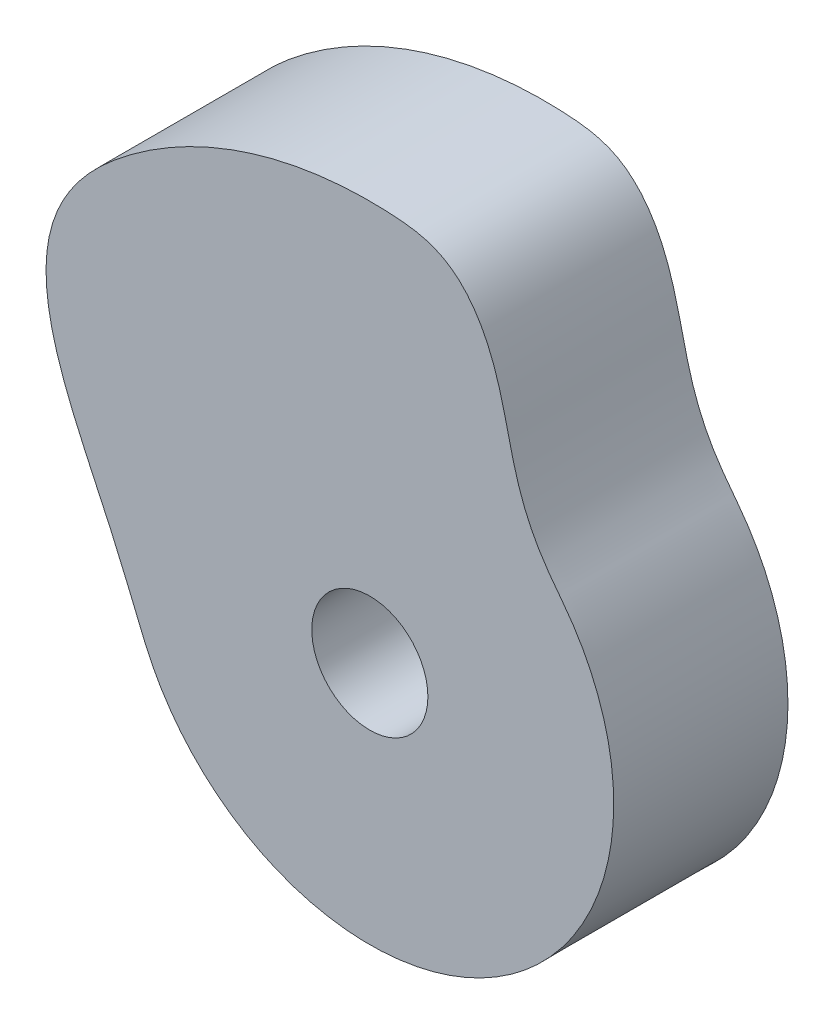
SolidWorks part; units mm, degrees
ref_plane "前视基准面" through (0, 0, 0) normal (0, 0, 1) x (1, 0, 0)
ref_plane "上视基准面" through (0, 0, 0) normal (0, 1, 0) x (1, 0, 0)
ref_plane "右视基准面" through (0, 0, 0) normal (1, 0, 0) x (0, 0, -1)
other "Configuration Table"
curve "曲线1"
sketch "草图1" plane through (0, 0, 0) normal (0, 0, 1) x (1, 0, 0)
  spline S0 degree 3 poles (34.8106, -23.5003) (35.0144, -23.1957) (35.2154, -22.8892) (35.4138, -22.581) (35.6096, -22.2712) (35.8026, -21.9596) (35.9929, -21.6463) (36.1804, -21.3313) (36.3651, -21.0148) (36.5472, -20.6967) (36.7264, -20.3769) (36.9028, -20.0557) (37.0764, -19.7328) (37.2472, -19.4086) (37.4151, -19.0828) (37.5801, -18.7555) (37.7425, -18.427) (37.9017, -18.0968) (38.0583, -17.7654) (38.2119, -17.4326) (38.3626, -17.0985) (38.5103, -16.7631) (38.6551, -16.4264) (38.797, -16.0884) (38.9359, -15.7492) (39.0719, -15.4089) (39.2049, -15.0673) (39.3348, -14.7246) (39.4618, -14.3808) (39.5858, -14.0359) (39.7068, -13.6899) (39.8248, -13.3429) (39.9397, -12.9949) (40.0516, -12.6459) (40.1604, -12.2958) (40.2662, -11.9449) (40.3689, -11.593) (40.4685, -11.2403) (40.565, -10.8867) (40.6585, -10.5323) (40.749, -10.1771) (40.8361, -9.8211) (40.9203, -9.4644) (41.0013, -9.107) (41.0792, -8.7488) (41.154, -8.39) (41.2256, -8.0306) (41.2941, -7.6705) (41.3596, -7.3099) (41.4217, -6.9487) (41.4808, -6.5869) (41.5367, -6.2247) (41.5894, -5.862) (41.639, -5.4988) (41.6854, -5.1353) (41.7286, -4.7713) (41.7688, -4.4069) (41.8055, -4.0423) (41.8393, -3.6773) (41.8697, -3.3121) (41.897, -2.9465) (41.9211, -2.5808) (41.9422, -2.2149) (41.9598, -1.8488) (41.9743, -1.4826) (41.9858, -1.1162) (41.9938, -0.7498) (41.9989, -0.3833) (42.0005, -0.0168) (41.999, 0.3497) (41.9945, 0.7162) (41.9865, 1.0826) (41.9755, 1.449) (41.9614, 1.8152) (41.9438, 2.1813) (41.9232, 2.5473) (41.8995, 2.913) (41.8723, 3.2786) (41.8422, 3.6438) (41.8087, 4.0088) (41.7723, 4.3735) (41.7324, 4.7379) (41.6895, 5.1019) (41.6434, 5.4655) (41.5941, 5.8287) (41.5416, 6.1915) (41.486, 6.5537) (41.4274, 6.9155) (41.3653, 7.2768) (41.3004, 7.6375) (41.232, 7.9976) (41.1608, 8.3571) (41.0862, 8.716) (41.0087, 9.0742) (40.9278, 9.4317) (40.8441, 9.7885) (40.757, 10.1445) (40.6669, 10.4998) (40.5737, 10.8543) (40.4775, 11.208) (40.3781, 11.5607) (40.2757, 11.9127) (40.1702, 12.2637) (40.0617, 12.6138) (39.9501, 12.9629) (39.8354, 13.311) (39.7177, 13.6582) (39.597, 14.0043) (39.4733, 14.3493) (39.3466, 14.6932) (39.2169, 15.036) (39.0842, 15.3776) (38.9485, 15.7181) (38.8099, 16.0574) (38.6683, 16.3955) (38.5237, 16.7323) (38.3762, 17.0678) (38.2258, 17.402) (38.0725, 17.7349) (37.9163, 18.0665) (37.7572, 18.3967) (37.5952, 18.7255) (37.4304, 19.0529) (37.2626, 19.3787) (37.0922, 19.7033) (36.9187, 20.0261) (36.7427, 20.3476) (36.5636, 20.6674) (36.382, 20.9858) (36.1973, 21.3023) (36.0102, 21.6175) (35.8201, 21.9309) (35.6274, 22.2426) (35.4319, 22.5527) (35.2338, 22.861) (35.0329, 23.1676) (34.8295, 23.4725) (34.6232, 23.7755) (34.4144, 24.0767) (34.203, 24.3761) (33.9886, 24.6743) (33.7684, 24.9748) (33.5375, 25.2841) (33.2916, 25.6091) (33.0288, 25.9537) (32.7492, 26.3186) (32.4537, 26.7043) (32.1438, 27.1114) (31.8205, 27.5399) (31.4853, 27.9903) (31.14, 28.4629) (30.7865, 28.9578) (30.4267, 29.4752) (30.0628, 30.0149) (29.6968, 30.5763) (29.3315, 31.159) (28.9688, 31.7618) (28.6109, 32.3835) (28.2604, 33.0228) (27.9187, 33.6777) (27.5878, 34.3463) (27.2692, 35.0265) (26.9637, 35.7162) (26.672, 36.4131) (26.3949, 37.1153) (26.132, 37.8206) (25.8834, 38.5275) (25.6483, 39.2342) (25.426, 39.9395) (25.2159, 40.6424) (25.0165, 41.342) (24.8269, 42.0377) (24.6459, 42.7291) (24.4721, 43.4159) (24.3046, 44.0981) (24.1418, 44.7756) (23.9829, 45.4484) (23.8264, 46.1166) (23.6714, 46.7804) (23.5168, 47.4399) (23.3618, 48.0951) (23.2052, 48.7459) (23.0463, 49.3926) (22.8843, 50.0349) (22.7182, 50.6727) (22.5479, 51.3059) (22.3719, 51.9341) (22.1904, 52.557) (22.0025, 53.1743) (21.8078, 53.7855) (21.6059, 54.39) (21.3968, 54.9874) (21.1798, 55.5769) (20.9551, 56.158) (20.7223, 56.7299) (20.4815, 57.292) (20.2329, 57.8437) (19.9762, 58.3841) (19.712, 58.9127) (19.4401, 59.4286) (19.161, 59.9313) (18.875, 60.42) (18.5825, 60.8943) (18.2839, 61.3537) (17.9798, 61.7977) (17.6703, 62.2257) (17.3562, 62.6375) (17.0379, 63.033) (16.7159, 63.4118) (16.3906, 63.7741) (16.0625, 64.1196) (15.7322, 64.4488) (15.3995, 64.7615) (15.0651, 65.0582) (14.7291, 65.3393) (14.3915, 65.6051) (14.0524, 65.8563) (13.7116, 66.0933) (13.3688, 66.3166) (13.0238, 66.5271) (12.6759, 66.725) (12.3249, 66.9116) (11.9698, 67.0867) (11.6099, 67.2514) (11.2445, 67.4062) (10.8724, 67.5513) (10.493, 67.6874) (10.1051, 67.8148) (9.7077, 67.9337) (9.2998, 68.0447) (8.8805, 68.1477) (8.4489, 68.2431) (8.0041, 68.331) (7.5452, 68.4117) (7.0716, 68.485) (6.5825, 68.5517) (6.0773, 68.6114) (5.5556, 68.6647) (5.0169, 68.7119) (4.4608, 68.7531) (3.8875, 68.7889) (3.2998, 68.8197) (2.7031, 68.8457) (2.1027, 68.8667) (1.5017, 68.8823) (0.9005, 68.8929) (0.2992, 68.8981) (-0.302, 68.8981) (-0.9032, 68.8928) (-1.5044, 68.8823) (-2.1054, 68.8666) (-2.7063, 68.8456) (-3.307, 68.8194) (-3.9074, 68.7879) (-4.5076, 68.7512) (-5.1074, 68.7092) (-5.7068, 68.662) (-6.3057, 68.6096) (-6.9042, 68.552) (-7.5022, 68.4891) (-8.0995, 68.4209) (-8.6963, 68.3478) (-9.2924, 68.2693) (-9.8878, 68.1856) (-10.4825, 68.0967) (-11.0763, 68.0025) (-11.6693, 67.9034) (-12.2615, 67.799) (-12.8527, 67.6894) (-13.4428, 67.5745) (-14.032, 67.4548) (-14.6201, 67.3296) (-15.2071, 67.1996) (-15.793, 67.0642) (-16.3776, 66.924) (-16.961, 66.7784) (-17.5431, 66.628) (-18.1238, 66.4722) (-18.7032, 66.3115) (-19.2812, 66.1458) (-19.8577, 65.975) (-20.4326, 65.7992) (-21.0061, 65.6184) (-21.5779, 65.4326) (-22.1481, 65.2418) (-22.7166, 65.0462) (-23.2833, 64.8454) (-23.8483, 64.6397) (-24.4115, 64.4291) (-24.9728, 64.2137) (-25.5322, 63.9933) (-26.0897, 63.768) (-26.6452, 63.5379) (-27.1986, 63.303) (-27.75, 63.0633) (-28.2992, 62.8187) (-28.8464, 62.5694) (-29.3912, 62.3151) (-29.934, 62.0564) (-30.4744, 61.7928) (-31.0125, 61.5245) (-31.5482, 61.2516) (-32.0815, 60.9739) (-32.6123, 60.6915) (-33.1407, 60.4047) (-33.6666, 60.1131) (-34.19, 59.8172) (-34.7105, 59.5164) (-35.2287, 59.2114) (-35.744, 58.9016) (-36.2566, 58.5874) (-36.7666, 58.2689) (-37.2735, 57.9457) (-37.7779, 57.6184) (-38.2792, 57.2864) (-38.7777, 56.9503) (-39.2732, 56.6096) (-39.7657, 56.2648) (-40.2552, 55.9156) (-40.7416, 55.5622) (-41.2249, 55.2047) (-41.7042, 54.8434) (-42.1787, 54.4792) (-42.6471, 54.1131) (-43.1086, 53.7451) (-43.5631, 53.3755) (-44.0103, 53.0042) (-44.4501, 52.631) (-44.8825, 52.2561) (-45.3071, 51.8794) (-45.7241, 51.5008) (-46.1331, 51.1205) (-46.5341, 50.7383) (-46.9269, 50.3542) (-47.3116, 49.9684) (-47.6879, 49.5808) (-48.0559, 49.1914) (-48.4153, 48.8003) (-48.7662, 48.4074) (-49.1084, 48.0128) (-49.442, 47.6165) (-49.7668, 47.2186) (-50.0829, 46.8191) (-50.3902, 46.418) (-50.6886, 46.0153) (-50.9782, 45.611) (-51.2588, 45.2053) (-51.5307, 44.7981) (-51.7936, 44.3892) (-52.0478, 43.979) (-52.2932, 43.5672) (-52.5297, 43.1539) (-52.7576, 42.7392) (-52.9768, 42.323) (-53.1871, 41.9051) (-53.389, 41.4858) (-53.5821, 41.0647) (-53.7669, 40.6421) (-53.943, 40.2178) (-54.1107, 39.7917) (-54.2702, 39.3638) (-54.4212, 38.934) (-54.564, 38.5023) (-54.6985, 38.0685) (-54.8249, 37.6327) (-54.9429, 37.1946) (-55.053, 36.7544) (-55.1549, 36.3118) (-55.2488, 35.8668) (-55.3346, 35.4193) (-55.4124, 34.9692) (-55.4824, 34.5165) (-55.5441, 34.0612) (-55.598, 33.6031) (-55.644, 33.1422) (-55.682, 32.6785) (-55.7122, 32.212) (-55.7344, 31.7426) (-55.7487, 31.2702) (-55.755, 30.795) (-55.7536, 30.3168) (-55.7444, 29.8358) (-55.7272, 29.3519) (-55.7023, 28.8651) (-55.6695, 28.3756) (-55.6293, 27.8833) (-55.5811, 27.3884) (-55.5253, 26.8908) (-55.4622, 26.3907) (-55.3912, 25.8882) (-55.3132, 25.3833) (-55.2274, 24.8762) (-55.1349, 24.3669) (-55.0347, 23.8556) (-54.9279, 23.3423) (-54.8137, 22.8273) (-54.6931, 22.3106) (-54.5656, 21.7923) (-54.4317, 21.2725) (-54.2914, 20.7514) (-54.1447, 20.2292) (-53.9921, 19.7059) (-53.8336, 19.1817) (-53.6694, 18.6566) (-53.4995, 18.1308) (-53.3244, 17.6045) (-53.1442, 17.0777) (-52.9588, 16.5506) (-52.769, 16.0231) (-52.5744, 15.4956) (-52.3755, 14.9679) (-52.1725, 14.4404) (-51.9656, 13.9129) (-51.755, 13.3856) (-51.5408, 12.8586) (-51.3236, 12.3319) (-51.103, 11.8058) (-50.8799, 11.2799) (-50.6539, 10.7547) (-50.4256, 10.23) (-50.1952, 9.7059) (-49.9627, 9.1825) (-49.7284, 8.6597) (-49.4927, 8.1375) (-49.2554, 7.6162) (-49.0171, 7.0956) (-48.7778, 6.5758) (-48.5378, 6.0567) (-48.2972, 5.5383) (-48.0562, 5.0209) (-47.8149, 4.5042) (-47.5739, 3.9883) (-47.3327, 3.4733) (-47.0921, 2.9591) (-46.8519, 2.4458) (-46.6124, 1.9333) (-46.3738, 1.4218) (-46.1361, 0.9113) (-45.8996, 0.4016) (-45.6644, -0.107) (-45.4306, -0.6144) (-45.1982, -1.1207) (-44.9679, -1.6258) (-44.739, -2.1296) (-44.5123, -2.632) (-44.2874, -3.1329) (-44.0648, -3.6322) (-43.8442, -4.1298) (-43.626, -4.6255) (-43.4101, -5.1192) (-43.1967, -5.6107) (-42.9856, -6.0998) (-42.7771, -6.5865) (-42.571, -7.0704) (-42.3676, -7.5515) (-42.1664, -8.0294) (-41.9679, -8.5041) (-41.7718, -8.9753) (-41.5782, -9.4427) (-41.387, -9.9063) (-41.1981, -10.3656) (-41.0114, -10.8206) (-40.8269, -11.2711) (-40.6446, -11.7168) (-40.4643, -12.1575) (-40.2858, -12.593) (-40.1091, -13.0231) (-39.9341, -13.4477) (-39.7608, -13.8666) (-39.5889, -14.2795) (-39.4183, -14.6864) (-39.249, -15.087) (-39.0807, -15.4813) (-38.9133, -15.869) (-38.7469, -16.25) (-38.5812, -16.6243) (-38.4162, -16.9917) (-38.2516, -17.3522) (-38.0874, -17.7055) (-37.9237, -18.0518) (-37.76, -18.391) (-37.596, -18.7241) (-37.4305, -19.0527) (-37.2626, -19.3787) (-37.0922, -19.7033) (-36.9187, -20.0261) (-36.7427, -20.3476) (-36.5636, -20.6674) (-36.382, -20.9858) (-36.1973, -21.3023) (-36.0102, -21.6175) (-35.8201, -21.9309) (-35.6274, -22.2426) (-35.4319, -22.5527) (-35.2338, -22.861) (-35.0329, -23.1676) (-34.8295, -23.4725) (-34.6232, -23.7755) (-34.4144, -24.0767) (-34.203, -24.3761) (-33.989, -24.6737) (-33.7725, -24.9694) (-33.5532, -25.2631) (-33.3316, -25.555) (-33.1072, -25.8448) (-32.8805, -26.1328) (-32.6511, -26.4187) (-32.4193, -26.7026) (-32.1851, -26.9846) (-31.9484, -27.2644) (-31.7092, -27.5421) (-31.4677, -27.8179) (-31.2237, -28.0913) (-30.9774, -28.3628) (-30.7287, -28.6319) (-30.4777, -28.8991) (-30.2243, -29.1639) (-29.9687, -29.4266) (-29.7108, -29.687) (-29.4506, -29.9451) (-29.1881, -30.2009) (-28.9235, -30.4546) (-28.6565, -30.7058) (-28.3876, -30.9547) (-28.1163, -31.2012) (-27.843, -31.4454) (-27.5676, -31.6872) (-27.2899, -31.9265) (-27.0103, -32.1635) (-26.7285, -32.3979) (-26.4449, -32.63) (-26.1591, -32.8595) (-25.8713, -33.0865) (-25.5816, -33.311) (-25.2899, -33.533) (-24.9964, -33.7525) (-24.7009, -33.9692) (-24.4036, -34.1835) (-24.1043, -34.3951) (-23.8032, -34.6042) (-23.5003, -34.8106) (-23.1957, -35.0144) (-22.8892, -35.2154) (-22.581, -35.4138) (-22.2712, -35.6096) (-21.9596, -35.8026) (-21.6463, -35.9929) (-21.3313, -36.1804) (-21.0148, -36.3651) (-20.6967, -36.5472) (-20.3769, -36.7264) (-20.0557, -36.9028) (-19.7328, -37.0764) (-19.4086, -37.2472) (-19.0828, -37.4151) (-18.7555, -37.5801) (-18.427, -37.7425) (-18.0968, -37.9017) (-17.7654, -38.0583) (-17.4326, -38.2119) (-17.0985, -38.3626) (-16.7631, -38.5103) (-16.4264, -38.6551) (-16.0884, -38.797) (-15.7492, -38.9359) (-15.4089, -39.0719) (-15.0673, -39.2049) (-14.7246, -39.3348) (-14.3808, -39.4618) (-14.0359, -39.5858) (-13.6899, -39.7068) (-13.3429, -39.8248) (-12.9949, -39.9397) (-12.6459, -40.0516) (-12.2958, -40.1604) (-11.9449, -40.2662) (-11.593, -40.3689) (-11.2403, -40.4685) (-10.8867, -40.565) (-10.5323, -40.6585) (-10.1771, -40.749) (-9.8211, -40.8361) (-9.4644, -40.9203) (-9.107, -41.0013) (-8.7488, -41.0792) (-8.39, -41.154) (-8.0306, -41.2256) (-7.6705, -41.2941) (-7.3099, -41.3596) (-6.9487, -41.4217) (-6.5869, -41.4808) (-6.2247, -41.5367) (-5.862, -41.5894) (-5.4988, -41.639) (-5.1353, -41.6854) (-4.7713, -41.7286) (-4.4069, -41.7688) (-4.0423, -41.8055) (-3.6773, -41.8393) (-3.3121, -41.8697) (-2.9465, -41.897) (-2.5808, -41.9211) (-2.2149, -41.9422) (-1.8488, -41.9598) (-1.4826, -41.9743) (-1.1162, -41.9858) (-0.7498, -41.9938) (-0.3833, -41.9989) (-0.0168, -42.0005) (0.3497, -41.999) (0.7162, -41.9945) (1.0826, -41.9865) (1.449, -41.9755) (1.8152, -41.9614) (2.1813, -41.9438) (2.5473, -41.9232) (2.913, -41.8995) (3.2786, -41.8723) (3.6438, -41.8422) (4.0088, -41.8087) (4.3735, -41.7723) (4.7379, -41.7324) (5.1019, -41.6895) (5.4655, -41.6434) (5.8287, -41.5941) (6.1915, -41.5416) (6.5537, -41.486) (6.9155, -41.4274) (7.2768, -41.3653) (7.6375, -41.3004) (7.9976, -41.232) (8.3571, -41.1608) (8.716, -41.0862) (9.0742, -41.0087) (9.4317, -40.9278) (9.7885, -40.8441) (10.1445, -40.757) (10.4998, -40.6669) (10.8543, -40.5737) (11.208, -40.4775) (11.5607, -40.3781) (11.9127, -40.2757) (12.2637, -40.1702) (12.6138, -40.0617) (12.9629, -39.9501) (13.311, -39.8354) (13.6582, -39.7177) (14.0043, -39.597) (14.3493, -39.4733) (14.6932, -39.3466) (15.036, -39.2169) (15.3776, -39.0842) (15.7181, -38.9485) (16.0574, -38.8099) (16.3955, -38.6683) (16.7323, -38.5237) (17.0678, -38.3762) (17.402, -38.2258) (17.7349, -38.0725) (18.0665, -37.9163) (18.3967, -37.7572) (18.7255, -37.5952) (19.0529, -37.4304) (19.3787, -37.2626) (19.7033, -37.0922) (20.0261, -36.9187) (20.3476, -36.7427) (20.6674, -36.5636) (20.9858, -36.382) (21.3023, -36.1973) (21.6175, -36.0102) (21.9309, -35.8201) (22.2426, -35.6274) (22.5527, -35.4319) (22.861, -35.2338) (23.1676, -35.0329) (23.4725, -34.8295) (23.7755, -34.6232) (24.0767, -34.4144) (24.3761, -34.203) (24.6737, -33.989) (24.9694, -33.7725) (25.2631, -33.5532) (25.555, -33.3316) (25.8448, -33.1072) (26.1328, -32.8805) (26.4187, -32.6511) (26.7026, -32.4193) (26.9846, -32.1851) (27.2644, -31.9484) (27.5421, -31.7092) (27.8179, -31.4677) (28.0913, -31.2237) (28.3628, -30.9774) (28.6319, -30.7287) (28.8991, -30.4777) (29.1639, -30.2243) (29.4266, -29.9687) (29.687, -29.7108) (29.9451, -29.4506) (30.2009, -29.1881) (30.4546, -28.9235) (30.7058, -28.6565) (30.9547, -28.3876) (31.2012, -28.1163) (31.4454, -27.843) (31.6872, -27.5676) (31.9265, -27.2899) (32.1635, -27.0103) (32.3979, -26.7285) (32.63, -26.4449) (32.8595, -26.1591) (33.0865, -25.8713) (33.311, -25.5816) (33.533, -25.2899) (33.7525, -24.9964) (33.9692, -24.7009) (34.1835, -24.4036) (34.3951, -24.1043) (34.6042, -23.8032) (34.8106, -23.5003) (35.0144, -23.1957) (35.2154, -22.8892) knots -0.003364 -0.002242 -0.001121 0 0.001121 0.002243 0.003364 0.004485 0.005606 0.006728 0.007849 0.00897 0.010091 0.011213 0.012334 0.013455 0.014576 0.015698 0.016819 0.01794 0.019061 0.020183 0.021304 0.022425 0.023546 0.024668 0.025789 0.02691 0.028031 0.029153 0.030274 0.031395 0.032516 0.033638 0.034759 0.03588 0.037001 0.038123 0.039244 0.040365 0.041486 0.042607 0.043729 0.04485 0.045971 0.047092 0.048214 0.049335 0.050456 0.051577 0.052699 0.05382 0.054941 0.056062 0.057184 0.058305 0.059426 0.060547 0.061669 0.06279 0.063911 0.065032 0.066154 0.067275 0.068396 0.069517 0.070638 0.07176 0.072881 0.074002 0.075123 0.076245 0.077366 0.078487 0.079608 0.08073 0.081851 0.082972 0.084093 0.085215 0.086336 0.087457 0.088578 0.0897 0.090821 0.091942 0.093063 0.094185 0.095306 0.096427 0.097548 0.09867 0.099791 0.100912 0.102033 0.103155 0.104276 0.105397 0.106518 0.10764 0.108761 0.109882 0.111003 0.112124 0.113246 0.114367 0.115488 0.11661 0.117731 0.118852 0.119973 0.121095 0.122216 0.123337 0.124458 0.125579 0.126701 0.127822 0.128943 0.130064 0.131186 0.132307 0.133428 0.13455 0.135671 0.136792 0.137913 0.139034 0.140156 0.141277 0.142398 0.143519 0.144641 0.145762 0.146883 0.148004 0.149126 0.150247 0.151368 0.152489 0.15361 0.154732 0.155853 0.156981 0.158151 0.159395 0.160721 0.162128 0.163615 0.16518 0.166823 0.168541 0.170333 0.172194 0.174124 0.176116 0.178168 0.180273 0.182428 0.184624 0.186857 0.189118 0.191403 0.193703 0.196012 0.198325 0.200635 0.202939 0.205233 0.207512 0.209774 0.212019 0.214245 0.216451 0.218637 0.220804 0.222952 0.225083 0.227198 0.229297 0.231382 0.233454 0.235513 0.237561 0.239598 0.241624 0.24364 0.245647 0.247642 0.249627 0.251601 0.253564 0.255514 0.25745 0.259372 0.261279 0.263168 0.265039 0.266891 0.268721 0.270529 0.272314 0.274073 0.275805 0.27751 0.279187 0.280833 0.282449 0.284033 0.285586 0.287107 0.288596 0.290053 0.29148 0.292876 0.294243 0.295582 0.296896 0.298185 0.299455 0.300705 0.30194 0.303163 0.304377 0.305587 0.306796 0.308009 0.309229 0.310461 0.311708 0.312976 0.314267 0.315587 0.316938 0.318324 0.319748 0.321213 0.322722 0.324278 0.325881 0.327535 0.329241 0.330999 0.332807 0.334642 0.336481 0.33832 0.340159 0.341999 0.343838 0.345677 0.347517 0.349356 0.351195 0.353035 0.354874 0.356713 0.358553 0.360392 0.362231 0.36407 0.36591 0.367749 0.369588 0.371428 0.373267 0.375106 0.376946 0.378785 0.380624 0.382464 0.384303 0.386142 0.387982 0.389821 0.39166 0.3935 0.395339 0.397178 0.399017 0.400857 0.402696 0.404535 0.406375 0.408214 0.410053 0.411893 0.413732 0.415571 0.417411 0.41925 0.421089 0.422929 0.424768 0.426607 0.428447 0.430286 0.432125 0.433964 0.435804 0.437643 0.439483 0.441322 0.443161 0.445001 0.44684 0.448679 0.450519 0.452358 0.454197 0.456036 0.457875 0.459715 0.461554 0.463394 0.465233 0.467072 0.468912 0.470751 0.47259 0.47443 0.476269 0.478108 0.479946 0.481778 0.483597 0.485403 0.487195 0.488973 0.490738 0.492488 0.494225 0.495947 0.497656 0.499351 0.501031 0.502698 0.504351 0.505989 0.507614 0.509226 0.510823 0.512408 0.513979 0.515537 0.517083 0.518616 0.520137 0.521646 0.523144 0.524631 0.526107 0.527573 0.52903 0.530477 0.531916 0.533347 0.53477 0.536187 0.537598 0.539003 0.540403 0.5418 0.543193 0.544584 0.545973 0.547361 0.548748 0.550136 0.551525 0.552916 0.55431 0.555707 0.557108 0.558513 0.559924 0.561341 0.562764 0.564194 0.565631 0.567077 0.568531 0.569993 0.571465 0.572946 0.574437 0.575937 0.577448 0.57897 0.580501 0.582043 0.583596 0.585159 0.586732 0.588315 0.589909 0.591513 0.593127 0.59475 0.596383 0.598025 0.599676 0.601336 0.603003 0.604679 0.606362 0.608052 0.609749 0.611453 0.613162 0.614877 0.616597 0.618323 0.620052 0.621785 0.623523 0.625263 0.627006 0.628751 0.630499 0.632248 0.633999 0.63575 0.637503 0.639255 0.641008 0.64276 0.644512 0.646263 0.648012 0.649761 0.651507 0.653251 0.654994 0.656733 0.65847 0.660204 0.661935 0.663661 0.665384 0.667103 0.668817 0.670527 0.672231 0.67393 0.675622 0.677309 0.678988 0.680661 0.682326 0.683984 0.685632 0.687271 0.688901 0.690521 0.69213 0.693728 0.695315 0.696889 0.69845 0.699999 0.701532 0.703052 0.704557 0.706046 0.707519 0.708976 0.710416 0.711839 0.713244 0.714631 0.716 0.717349 0.71868 0.719991 0.721283 0.722555 0.723807 0.72504 0.726252 0.727444 0.728616 0.729767 0.7309 0.732023 0.733144 0.734265 0.735387 0.736508 0.737629 0.73875 0.739872 0.740993 0.742114 0.743235 0.744356 0.745478 0.746599 0.74772 0.748842 0.749963 0.751084 0.752205 0.753327 0.754448 0.755569 0.75669 0.757812 0.758933 0.760054 0.761175 0.762296 0.763418 0.764539 0.76566 0.766781 0.767903 0.769024 0.770145 0.771266 0.772388 0.773509 0.77463 0.775751 0.776873 0.777994 0.779115 0.780236 0.781358 0.782479 0.7836 0.784721 0.785843 0.786964 0.788085 0.789206 0.790328 0.791449 0.79257 0.793691 0.794812 0.795934 0.797055 0.798176 0.799298 0.800419 0.80154 0.802661 0.803783 0.804904 0.806025 0.807146 0.808267 0.809389 0.81051 0.811631 0.812752 0.813874 0.814995 0.816116 0.817237 0.818359 0.81948 0.820601 0.821722 0.822844 0.823965 0.825086 0.826208 0.827329 0.82845 0.829571 0.830692 0.831814 0.832935 0.834056 0.835177 0.836299 0.83742 0.838541 0.839662 0.840784 0.841905 0.843026 0.844147 0.845268 0.84639 0.847511 0.848632 0.849753 0.850875 0.851996 0.853117 0.854238 0.85536 0.856481 0.857602 0.858723 0.859845 0.860966 0.862087 0.863208 0.86433 0.865451 0.866572 0.867693 0.868815 0.869936 0.871057 0.872178 0.8733 0.874421 0.875542 0.876663 0.877785 0.878906 0.880027 0.881148 0.882269 0.883391 0.884512 0.885633 0.886755 0.887876 0.888997 0.890118 0.891239 0.892361 0.893482 0.894603 0.895725 0.896846 0.897967 0.899088 0.90021 0.901331 0.902452 0.903573 0.904694 0.905816 0.906937 0.908058 0.909179 0.910301 0.911422 0.912543 0.913664 0.914786 0.915907 0.917028 0.91815 0.919271 0.920392 0.921513 0.922634 0.923756 0.924877 0.925998 0.927119 0.928241 0.929362 0.930483 0.931604 0.932726 0.933847 0.934968 0.936089 0.937211 0.938332 0.939453 0.940574 0.941695 0.942817 0.943938 0.945059 0.94618 0.947302 0.948423 0.949544 0.950665 0.951787 0.952908 0.954029 0.95515 0.956272 0.957393 0.958514 0.959635 0.960757 0.961878 0.962999 0.96412 0.965242 0.966363 0.967484 0.968605 0.969726 0.970848 0.971969 0.97309 0.974211 0.975333 0.976454 0.977575 0.978697 0.979818 0.980939 0.98206 0.983181 0.984303 0.985424 0.986545 0.987667 0.988788 0.989909 0.99103 0.992152 0.993273 0.994394 0.995515 0.996636 0.997758 0.998879 1 1.001121 1.002243 1.003364 only from (35.0139, -23.1954) to (35.0139, -23.1954) construction
  spline S1 degree 3 poles (34.8106, -23.5003) (35.0144, -23.1957) (35.2154, -22.8892) (35.4138, -22.581) (35.6096, -22.2712) (35.8026, -21.9596) (35.9929, -21.6463) (36.1804, -21.3313) (36.3651, -21.0148) (36.5472, -20.6967) (36.7264, -20.3769) (36.9028, -20.0557) (37.0764, -19.7328) (37.2472, -19.4086) (37.4151, -19.0828) (37.5801, -18.7555) (37.7425, -18.427) (37.9017, -18.0968) (38.0583, -17.7654) (38.2119, -17.4326) (38.3626, -17.0985) (38.5103, -16.7631) (38.6551, -16.4264) (38.797, -16.0884) (38.9359, -15.7492) (39.0719, -15.4089) (39.2049, -15.0673) (39.3348, -14.7246) (39.4618, -14.3808) (39.5858, -14.0359) (39.7068, -13.6899) (39.8248, -13.3429) (39.9397, -12.9949) (40.0516, -12.6459) (40.1604, -12.2958) (40.2662, -11.9449) (40.3689, -11.593) (40.4685, -11.2403) (40.565, -10.8867) (40.6585, -10.5323) (40.749, -10.1771) (40.8361, -9.8211) (40.9203, -9.4644) (41.0013, -9.107) (41.0792, -8.7488) (41.154, -8.39) (41.2256, -8.0306) (41.2941, -7.6705) (41.3596, -7.3099) (41.4217, -6.9487) (41.4808, -6.5869) (41.5367, -6.2247) (41.5894, -5.862) (41.639, -5.4988) (41.6854, -5.1353) (41.7286, -4.7713) (41.7688, -4.4069) (41.8055, -4.0423) (41.8393, -3.6773) (41.8697, -3.3121) (41.897, -2.9465) (41.9211, -2.5808) (41.9422, -2.2149) (41.9598, -1.8488) (41.9743, -1.4826) (41.9858, -1.1162) (41.9938, -0.7498) (41.9989, -0.3833) (42.0005, -0.0168) (41.999, 0.3497) (41.9945, 0.7162) (41.9865, 1.0826) (41.9755, 1.449) (41.9614, 1.8152) (41.9438, 2.1813) (41.9232, 2.5473) (41.8995, 2.913) (41.8723, 3.2786) (41.8422, 3.6438) (41.8087, 4.0088) (41.7723, 4.3735) (41.7324, 4.7379) (41.6895, 5.1019) (41.6434, 5.4655) (41.5941, 5.8287) (41.5416, 6.1915) (41.486, 6.5537) (41.4274, 6.9155) (41.3653, 7.2768) (41.3004, 7.6375) (41.232, 7.9976) (41.1608, 8.3571) (41.0862, 8.716) (41.0087, 9.0742) (40.9278, 9.4317) (40.8441, 9.7885) (40.757, 10.1445) (40.6669, 10.4998) (40.5737, 10.8543) (40.4775, 11.208) (40.3781, 11.5607) (40.2757, 11.9127) (40.1702, 12.2637) (40.0617, 12.6138) (39.9501, 12.9629) (39.8354, 13.311) (39.7177, 13.6582) (39.597, 14.0043) (39.4733, 14.3493) (39.3466, 14.6932) (39.2169, 15.036) (39.0842, 15.3776) (38.9485, 15.7181) (38.8099, 16.0574) (38.6683, 16.3955) (38.5237, 16.7323) (38.3762, 17.0678) (38.2258, 17.402) (38.0725, 17.7349) (37.9163, 18.0665) (37.7572, 18.3967) (37.5952, 18.7255) (37.4304, 19.0529) (37.2626, 19.3787) (37.0922, 19.7033) (36.9187, 20.0261) (36.7427, 20.3476) (36.5636, 20.6674) (36.382, 20.9858) (36.1973, 21.3023) (36.0102, 21.6175) (35.8201, 21.9309) (35.6274, 22.2426) (35.4319, 22.5527) (35.2338, 22.861) (35.0329, 23.1676) (34.8295, 23.4725) (34.6232, 23.7755) (34.4144, 24.0767) (34.203, 24.3761) (33.9886, 24.6743) (33.7684, 24.9748) (33.5375, 25.2841) (33.2916, 25.6091) (33.0288, 25.9537) (32.7492, 26.3186) (32.4537, 26.7043) (32.1438, 27.1114) (31.8205, 27.5399) (31.4853, 27.9903) (31.14, 28.4629) (30.7865, 28.9578) (30.4267, 29.4752) (30.0628, 30.0149) (29.6968, 30.5763) (29.3315, 31.159) (28.9688, 31.7618) (28.6109, 32.3835) (28.2604, 33.0228) (27.9187, 33.6777) (27.5878, 34.3463) (27.2692, 35.0265) (26.9637, 35.7162) (26.672, 36.4131) (26.3949, 37.1153) (26.132, 37.8206) (25.8834, 38.5275) (25.6483, 39.2342) (25.426, 39.9395) (25.2159, 40.6424) (25.0165, 41.342) (24.8269, 42.0377) (24.6459, 42.7291) (24.4721, 43.4159) (24.3046, 44.0981) (24.1418, 44.7756) (23.9829, 45.4484) (23.8264, 46.1166) (23.6714, 46.7804) (23.5168, 47.4399) (23.3618, 48.0951) (23.2052, 48.7459) (23.0463, 49.3926) (22.8843, 50.0349) (22.7182, 50.6727) (22.5479, 51.3059) (22.3719, 51.9341) (22.1904, 52.557) (22.0025, 53.1743) (21.8078, 53.7855) (21.6059, 54.39) (21.3968, 54.9874) (21.1798, 55.5769) (20.9551, 56.158) (20.7223, 56.7299) (20.4815, 57.292) (20.2329, 57.8437) (19.9762, 58.3841) (19.712, 58.9127) (19.4401, 59.4286) (19.161, 59.9313) (18.875, 60.42) (18.5825, 60.8943) (18.2839, 61.3537) (17.9798, 61.7977) (17.6703, 62.2257) (17.3562, 62.6375) (17.0379, 63.033) (16.7159, 63.4118) (16.3906, 63.7741) (16.0625, 64.1196) (15.7322, 64.4488) (15.3995, 64.7615) (15.0651, 65.0582) (14.7291, 65.3393) (14.3915, 65.6051) (14.0524, 65.8563) (13.7116, 66.0933) (13.3688, 66.3166) (13.0238, 66.5271) (12.6759, 66.725) (12.3249, 66.9116) (11.9698, 67.0867) (11.6099, 67.2514) (11.2445, 67.4062) (10.8724, 67.5513) (10.493, 67.6874) (10.1051, 67.8148) (9.7077, 67.9337) (9.2998, 68.0447) (8.8805, 68.1477) (8.4489, 68.2431) (8.0041, 68.331) (7.5452, 68.4117) (7.0716, 68.485) (6.5825, 68.5517) (6.0773, 68.6114) (5.5556, 68.6647) (5.0169, 68.7119) (4.4608, 68.7531) (3.8875, 68.7889) (3.2998, 68.8197) (2.7031, 68.8457) (2.1027, 68.8667) (1.5017, 68.8823) (0.9005, 68.8929) (0.2992, 68.8981) (-0.302, 68.8981) (-0.9032, 68.8928) (-1.5044, 68.8823) (-2.1054, 68.8666) (-2.7063, 68.8456) (-3.307, 68.8194) (-3.9074, 68.7879) (-4.5076, 68.7512) (-5.1074, 68.7092) (-5.7068, 68.662) (-6.3057, 68.6096) (-6.9042, 68.552) (-7.5022, 68.4891) (-8.0995, 68.4209) (-8.6963, 68.3478) (-9.2924, 68.2693) (-9.8878, 68.1856) (-10.4825, 68.0967) (-11.0763, 68.0025) (-11.6693, 67.9034) (-12.2615, 67.799) (-12.8527, 67.6894) (-13.4428, 67.5745) (-14.032, 67.4548) (-14.6201, 67.3296) (-15.2071, 67.1996) (-15.793, 67.0642) (-16.3776, 66.924) (-16.961, 66.7784) (-17.5431, 66.628) (-18.1238, 66.4722) (-18.7032, 66.3115) (-19.2812, 66.1458) (-19.8577, 65.975) (-20.4326, 65.7992) (-21.0061, 65.6184) (-21.5779, 65.4326) (-22.1481, 65.2418) (-22.7166, 65.0462) (-23.2833, 64.8454) (-23.8483, 64.6397) (-24.4115, 64.4291) (-24.9728, 64.2137) (-25.5322, 63.9933) (-26.0897, 63.768) (-26.6452, 63.5379) (-27.1986, 63.303) (-27.75, 63.0633) (-28.2992, 62.8187) (-28.8464, 62.5694) (-29.3912, 62.3151) (-29.934, 62.0564) (-30.4744, 61.7928) (-31.0125, 61.5245) (-31.5482, 61.2516) (-32.0815, 60.9739) (-32.6123, 60.6915) (-33.1407, 60.4047) (-33.6666, 60.1131) (-34.19, 59.8172) (-34.7105, 59.5164) (-35.2287, 59.2114) (-35.744, 58.9016) (-36.2566, 58.5874) (-36.7666, 58.2689) (-37.2735, 57.9457) (-37.7779, 57.6184) (-38.2792, 57.2864) (-38.7777, 56.9503) (-39.2732, 56.6096) (-39.7657, 56.2648) (-40.2552, 55.9156) (-40.7416, 55.5622) (-41.2249, 55.2047) (-41.7042, 54.8434) (-42.1787, 54.4792) (-42.6471, 54.1131) (-43.1086, 53.7451) (-43.5631, 53.3755) (-44.0103, 53.0042) (-44.4501, 52.631) (-44.8825, 52.2561) (-45.3071, 51.8794) (-45.7241, 51.5008) (-46.1331, 51.1205) (-46.5341, 50.7383) (-46.9269, 50.3542) (-47.3116, 49.9684) (-47.6879, 49.5808) (-48.0559, 49.1914) (-48.4153, 48.8003) (-48.7662, 48.4074) (-49.1084, 48.0128) (-49.442, 47.6165) (-49.7668, 47.2186) (-50.0829, 46.8191) (-50.3902, 46.418) (-50.6886, 46.0153) (-50.9782, 45.611) (-51.2588, 45.2053) (-51.5307, 44.7981) (-51.7936, 44.3892) (-52.0478, 43.979) (-52.2932, 43.5672) (-52.5297, 43.1539) (-52.7576, 42.7392) (-52.9768, 42.323) (-53.1871, 41.9051) (-53.389, 41.4858) (-53.5821, 41.0647) (-53.7669, 40.6421) (-53.943, 40.2178) (-54.1107, 39.7917) (-54.2702, 39.3638) (-54.4212, 38.934) (-54.564, 38.5023) (-54.6985, 38.0685) (-54.8249, 37.6327) (-54.9429, 37.1946) (-55.053, 36.7544) (-55.1549, 36.3118) (-55.2488, 35.8668) (-55.3346, 35.4193) (-55.4124, 34.9692) (-55.4824, 34.5165) (-55.5441, 34.0612) (-55.598, 33.6031) (-55.644, 33.1422) (-55.682, 32.6785) (-55.7122, 32.212) (-55.7344, 31.7426) (-55.7487, 31.2702) (-55.755, 30.795) (-55.7536, 30.3168) (-55.7444, 29.8358) (-55.7272, 29.3519) (-55.7023, 28.8651) (-55.6695, 28.3756) (-55.6293, 27.8833) (-55.5811, 27.3884) (-55.5253, 26.8908) (-55.4622, 26.3907) (-55.3912, 25.8882) (-55.3132, 25.3833) (-55.2274, 24.8762) (-55.1349, 24.3669) (-55.0347, 23.8556) (-54.9279, 23.3423) (-54.8137, 22.8273) (-54.6931, 22.3106) (-54.5656, 21.7923) (-54.4317, 21.2725) (-54.2914, 20.7514) (-54.1447, 20.2292) (-53.9921, 19.7059) (-53.8336, 19.1817) (-53.6694, 18.6566) (-53.4995, 18.1308) (-53.3244, 17.6045) (-53.1442, 17.0777) (-52.9588, 16.5506) (-52.769, 16.0231) (-52.5744, 15.4956) (-52.3755, 14.9679) (-52.1725, 14.4404) (-51.9656, 13.9129) (-51.755, 13.3856) (-51.5408, 12.8586) (-51.3236, 12.3319) (-51.103, 11.8058) (-50.8799, 11.2799) (-50.6539, 10.7547) (-50.4256, 10.23) (-50.1952, 9.7059) (-49.9627, 9.1825) (-49.7284, 8.6597) (-49.4927, 8.1375) (-49.2554, 7.6162) (-49.0171, 7.0956) (-48.7778, 6.5758) (-48.5378, 6.0567) (-48.2972, 5.5383) (-48.0562, 5.0209) (-47.8149, 4.5042) (-47.5739, 3.9883) (-47.3327, 3.4733) (-47.0921, 2.9591) (-46.8519, 2.4458) (-46.6124, 1.9333) (-46.3738, 1.4218) (-46.1361, 0.9113) (-45.8996, 0.4016) (-45.6644, -0.107) (-45.4306, -0.6144) (-45.1982, -1.1207) (-44.9679, -1.6258) (-44.739, -2.1296) (-44.5123, -2.632) (-44.2874, -3.1329) (-44.0648, -3.6322) (-43.8442, -4.1298) (-43.626, -4.6255) (-43.4101, -5.1192) (-43.1967, -5.6107) (-42.9856, -6.0998) (-42.7771, -6.5865) (-42.571, -7.0704) (-42.3676, -7.5515) (-42.1664, -8.0294) (-41.9679, -8.5041) (-41.7718, -8.9753) (-41.5782, -9.4427) (-41.387, -9.9063) (-41.1981, -10.3656) (-41.0114, -10.8206) (-40.8269, -11.2711) (-40.6446, -11.7168) (-40.4643, -12.1575) (-40.2858, -12.593) (-40.1091, -13.0231) (-39.9341, -13.4477) (-39.7608, -13.8666) (-39.5889, -14.2795) (-39.4183, -14.6864) (-39.249, -15.087) (-39.0807, -15.4813) (-38.9133, -15.869) (-38.7469, -16.25) (-38.5812, -16.6243) (-38.4162, -16.9917) (-38.2516, -17.3522) (-38.0874, -17.7055) (-37.9237, -18.0518) (-37.76, -18.391) (-37.596, -18.7241) (-37.4305, -19.0527) (-37.2626, -19.3787) (-37.0922, -19.7033) (-36.9187, -20.0261) (-36.7427, -20.3476) (-36.5636, -20.6674) (-36.382, -20.9858) (-36.1973, -21.3023) (-36.0102, -21.6175) (-35.8201, -21.9309) (-35.6274, -22.2426) (-35.4319, -22.5527) (-35.2338, -22.861) (-35.0329, -23.1676) (-34.8295, -23.4725) (-34.6232, -23.7755) (-34.4144, -24.0767) (-34.203, -24.3761) (-33.989, -24.6737) (-33.7725, -24.9694) (-33.5532, -25.2631) (-33.3316, -25.555) (-33.1072, -25.8448) (-32.8805, -26.1328) (-32.6511, -26.4187) (-32.4193, -26.7026) (-32.1851, -26.9846) (-31.9484, -27.2644) (-31.7092, -27.5421) (-31.4677, -27.8179) (-31.2237, -28.0913) (-30.9774, -28.3628) (-30.7287, -28.6319) (-30.4777, -28.8991) (-30.2243, -29.1639) (-29.9687, -29.4266) (-29.7108, -29.687) (-29.4506, -29.9451) (-29.1881, -30.2009) (-28.9235, -30.4546) (-28.6565, -30.7058) (-28.3876, -30.9547) (-28.1163, -31.2012) (-27.843, -31.4454) (-27.5676, -31.6872) (-27.2899, -31.9265) (-27.0103, -32.1635) (-26.7285, -32.3979) (-26.4449, -32.63) (-26.1591, -32.8595) (-25.8713, -33.0865) (-25.5816, -33.311) (-25.2899, -33.533) (-24.9964, -33.7525) (-24.7009, -33.9692) (-24.4036, -34.1835) (-24.1043, -34.3951) (-23.8032, -34.6042) (-23.5003, -34.8106) (-23.1957, -35.0144) (-22.8892, -35.2154) (-22.581, -35.4138) (-22.2712, -35.6096) (-21.9596, -35.8026) (-21.6463, -35.9929) (-21.3313, -36.1804) (-21.0148, -36.3651) (-20.6967, -36.5472) (-20.3769, -36.7264) (-20.0557, -36.9028) (-19.7328, -37.0764) (-19.4086, -37.2472) (-19.0828, -37.4151) (-18.7555, -37.5801) (-18.427, -37.7425) (-18.0968, -37.9017) (-17.7654, -38.0583) (-17.4326, -38.2119) (-17.0985, -38.3626) (-16.7631, -38.5103) (-16.4264, -38.6551) (-16.0884, -38.797) (-15.7492, -38.9359) (-15.4089, -39.0719) (-15.0673, -39.2049) (-14.7246, -39.3348) (-14.3808, -39.4618) (-14.0359, -39.5858) (-13.6899, -39.7068) (-13.3429, -39.8248) (-12.9949, -39.9397) (-12.6459, -40.0516) (-12.2958, -40.1604) (-11.9449, -40.2662) (-11.593, -40.3689) (-11.2403, -40.4685) (-10.8867, -40.565) (-10.5323, -40.6585) (-10.1771, -40.749) (-9.8211, -40.8361) (-9.4644, -40.9203) (-9.107, -41.0013) (-8.7488, -41.0792) (-8.39, -41.154) (-8.0306, -41.2256) (-7.6705, -41.2941) (-7.3099, -41.3596) (-6.9487, -41.4217) (-6.5869, -41.4808) (-6.2247, -41.5367) (-5.862, -41.5894) (-5.4988, -41.639) (-5.1353, -41.6854) (-4.7713, -41.7286) (-4.4069, -41.7688) (-4.0423, -41.8055) (-3.6773, -41.8393) (-3.3121, -41.8697) (-2.9465, -41.897) (-2.5808, -41.9211) (-2.2149, -41.9422) (-1.8488, -41.9598) (-1.4826, -41.9743) (-1.1162, -41.9858) (-0.7498, -41.9938) (-0.3833, -41.9989) (-0.0168, -42.0005) (0.3497, -41.999) (0.7162, -41.9945) (1.0826, -41.9865) (1.449, -41.9755) (1.8152, -41.9614) (2.1813, -41.9438) (2.5473, -41.9232) (2.913, -41.8995) (3.2786, -41.8723) (3.6438, -41.8422) (4.0088, -41.8087) (4.3735, -41.7723) (4.7379, -41.7324) (5.1019, -41.6895) (5.4655, -41.6434) (5.8287, -41.5941) (6.1915, -41.5416) (6.5537, -41.486) (6.9155, -41.4274) (7.2768, -41.3653) (7.6375, -41.3004) (7.9976, -41.232) (8.3571, -41.1608) (8.716, -41.0862) (9.0742, -41.0087) (9.4317, -40.9278) (9.7885, -40.8441) (10.1445, -40.757) (10.4998, -40.6669) (10.8543, -40.5737) (11.208, -40.4775) (11.5607, -40.3781) (11.9127, -40.2757) (12.2637, -40.1702) (12.6138, -40.0617) (12.9629, -39.9501) (13.311, -39.8354) (13.6582, -39.7177) (14.0043, -39.597) (14.3493, -39.4733) (14.6932, -39.3466) (15.036, -39.2169) (15.3776, -39.0842) (15.7181, -38.9485) (16.0574, -38.8099) (16.3955, -38.6683) (16.7323, -38.5237) (17.0678, -38.3762) (17.402, -38.2258) (17.7349, -38.0725) (18.0665, -37.9163) (18.3967, -37.7572) (18.7255, -37.5952) (19.0529, -37.4304) (19.3787, -37.2626) (19.7033, -37.0922) (20.0261, -36.9187) (20.3476, -36.7427) (20.6674, -36.5636) (20.9858, -36.382) (21.3023, -36.1973) (21.6175, -36.0102) (21.9309, -35.8201) (22.2426, -35.6274) (22.5527, -35.4319) (22.861, -35.2338) (23.1676, -35.0329) (23.4725, -34.8295) (23.7755, -34.6232) (24.0767, -34.4144) (24.3761, -34.203) (24.6737, -33.989) (24.9694, -33.7725) (25.2631, -33.5532) (25.555, -33.3316) (25.8448, -33.1072) (26.1328, -32.8805) (26.4187, -32.6511) (26.7026, -32.4193) (26.9846, -32.1851) (27.2644, -31.9484) (27.5421, -31.7092) (27.8179, -31.4677) (28.0913, -31.2237) (28.3628, -30.9774) (28.6319, -30.7287) (28.8991, -30.4777) (29.1639, -30.2243) (29.4266, -29.9687) (29.687, -29.7108) (29.9451, -29.4506) (30.2009, -29.1881) (30.4546, -28.9235) (30.7058, -28.6565) (30.9547, -28.3876) (31.2012, -28.1163) (31.4454, -27.843) (31.6872, -27.5676) (31.9265, -27.2899) (32.1635, -27.0103) (32.3979, -26.7285) (32.63, -26.4449) (32.8595, -26.1591) (33.0865, -25.8713) (33.311, -25.5816) (33.533, -25.2899) (33.7525, -24.9964) (33.9692, -24.7009) (34.1835, -24.4036) (34.3951, -24.1043) (34.6042, -23.8032) (34.8106, -23.5003) (35.0144, -23.1957) (35.2154, -22.8892) knots -0.003364 -0.002242 -0.001121 0 0.001121 0.002243 0.003364 0.004485 0.005606 0.006728 0.007849 0.00897 0.010091 0.011213 0.012334 0.013455 0.014576 0.015698 0.016819 0.01794 0.019061 0.020183 0.021304 0.022425 0.023546 0.024668 0.025789 0.02691 0.028031 0.029153 0.030274 0.031395 0.032516 0.033638 0.034759 0.03588 0.037001 0.038123 0.039244 0.040365 0.041486 0.042607 0.043729 0.04485 0.045971 0.047092 0.048214 0.049335 0.050456 0.051577 0.052699 0.05382 0.054941 0.056062 0.057184 0.058305 0.059426 0.060547 0.061669 0.06279 0.063911 0.065032 0.066154 0.067275 0.068396 0.069517 0.070638 0.07176 0.072881 0.074002 0.075123 0.076245 0.077366 0.078487 0.079608 0.08073 0.081851 0.082972 0.084093 0.085215 0.086336 0.087457 0.088578 0.0897 0.090821 0.091942 0.093063 0.094185 0.095306 0.096427 0.097548 0.09867 0.099791 0.100912 0.102033 0.103155 0.104276 0.105397 0.106518 0.10764 0.108761 0.109882 0.111003 0.112124 0.113246 0.114367 0.115488 0.11661 0.117731 0.118852 0.119973 0.121095 0.122216 0.123337 0.124458 0.125579 0.126701 0.127822 0.128943 0.130064 0.131186 0.132307 0.133428 0.13455 0.135671 0.136792 0.137913 0.139034 0.140156 0.141277 0.142398 0.143519 0.144641 0.145762 0.146883 0.148004 0.149126 0.150247 0.151368 0.152489 0.15361 0.154732 0.155853 0.156981 0.158151 0.159395 0.160721 0.162128 0.163615 0.16518 0.166823 0.168541 0.170333 0.172194 0.174124 0.176116 0.178168 0.180273 0.182428 0.184624 0.186857 0.189118 0.191403 0.193703 0.196012 0.198325 0.200635 0.202939 0.205233 0.207512 0.209774 0.212019 0.214245 0.216451 0.218637 0.220804 0.222952 0.225083 0.227198 0.229297 0.231382 0.233454 0.235513 0.237561 0.239598 0.241624 0.24364 0.245647 0.247642 0.249627 0.251601 0.253564 0.255514 0.25745 0.259372 0.261279 0.263168 0.265039 0.266891 0.268721 0.270529 0.272314 0.274073 0.275805 0.27751 0.279187 0.280833 0.282449 0.284033 0.285586 0.287107 0.288596 0.290053 0.29148 0.292876 0.294243 0.295582 0.296896 0.298185 0.299455 0.300705 0.30194 0.303163 0.304377 0.305587 0.306796 0.308009 0.309229 0.310461 0.311708 0.312976 0.314267 0.315587 0.316938 0.318324 0.319748 0.321213 0.322722 0.324278 0.325881 0.327535 0.329241 0.330999 0.332807 0.334642 0.336481 0.33832 0.340159 0.341999 0.343838 0.345677 0.347517 0.349356 0.351195 0.353035 0.354874 0.356713 0.358553 0.360392 0.362231 0.36407 0.36591 0.367749 0.369588 0.371428 0.373267 0.375106 0.376946 0.378785 0.380624 0.382464 0.384303 0.386142 0.387982 0.389821 0.39166 0.3935 0.395339 0.397178 0.399017 0.400857 0.402696 0.404535 0.406375 0.408214 0.410053 0.411893 0.413732 0.415571 0.417411 0.41925 0.421089 0.422929 0.424768 0.426607 0.428447 0.430286 0.432125 0.433964 0.435804 0.437643 0.439483 0.441322 0.443161 0.445001 0.44684 0.448679 0.450519 0.452358 0.454197 0.456036 0.457875 0.459715 0.461554 0.463394 0.465233 0.467072 0.468912 0.470751 0.47259 0.47443 0.476269 0.478108 0.479946 0.481778 0.483597 0.485403 0.487195 0.488973 0.490738 0.492488 0.494225 0.495947 0.497656 0.499351 0.501031 0.502698 0.504351 0.505989 0.507614 0.509226 0.510823 0.512408 0.513979 0.515537 0.517083 0.518616 0.520137 0.521646 0.523144 0.524631 0.526107 0.527573 0.52903 0.530477 0.531916 0.533347 0.53477 0.536187 0.537598 0.539003 0.540403 0.5418 0.543193 0.544584 0.545973 0.547361 0.548748 0.550136 0.551525 0.552916 0.55431 0.555707 0.557108 0.558513 0.559924 0.561341 0.562764 0.564194 0.565631 0.567077 0.568531 0.569993 0.571465 0.572946 0.574437 0.575937 0.577448 0.57897 0.580501 0.582043 0.583596 0.585159 0.586732 0.588315 0.589909 0.591513 0.593127 0.59475 0.596383 0.598025 0.599676 0.601336 0.603003 0.604679 0.606362 0.608052 0.609749 0.611453 0.613162 0.614877 0.616597 0.618323 0.620052 0.621785 0.623523 0.625263 0.627006 0.628751 0.630499 0.632248 0.633999 0.63575 0.637503 0.639255 0.641008 0.64276 0.644512 0.646263 0.648012 0.649761 0.651507 0.653251 0.654994 0.656733 0.65847 0.660204 0.661935 0.663661 0.665384 0.667103 0.668817 0.670527 0.672231 0.67393 0.675622 0.677309 0.678988 0.680661 0.682326 0.683984 0.685632 0.687271 0.688901 0.690521 0.69213 0.693728 0.695315 0.696889 0.69845 0.699999 0.701532 0.703052 0.704557 0.706046 0.707519 0.708976 0.710416 0.711839 0.713244 0.714631 0.716 0.717349 0.71868 0.719991 0.721283 0.722555 0.723807 0.72504 0.726252 0.727444 0.728616 0.729767 0.7309 0.732023 0.733144 0.734265 0.735387 0.736508 0.737629 0.73875 0.739872 0.740993 0.742114 0.743235 0.744356 0.745478 0.746599 0.74772 0.748842 0.749963 0.751084 0.752205 0.753327 0.754448 0.755569 0.75669 0.757812 0.758933 0.760054 0.761175 0.762296 0.763418 0.764539 0.76566 0.766781 0.767903 0.769024 0.770145 0.771266 0.772388 0.773509 0.77463 0.775751 0.776873 0.777994 0.779115 0.780236 0.781358 0.782479 0.7836 0.784721 0.785843 0.786964 0.788085 0.789206 0.790328 0.791449 0.79257 0.793691 0.794812 0.795934 0.797055 0.798176 0.799298 0.800419 0.80154 0.802661 0.803783 0.804904 0.806025 0.807146 0.808267 0.809389 0.81051 0.811631 0.812752 0.813874 0.814995 0.816116 0.817237 0.818359 0.81948 0.820601 0.821722 0.822844 0.823965 0.825086 0.826208 0.827329 0.82845 0.829571 0.830692 0.831814 0.832935 0.834056 0.835177 0.836299 0.83742 0.838541 0.839662 0.840784 0.841905 0.843026 0.844147 0.845268 0.84639 0.847511 0.848632 0.849753 0.850875 0.851996 0.853117 0.854238 0.85536 0.856481 0.857602 0.858723 0.859845 0.860966 0.862087 0.863208 0.86433 0.865451 0.866572 0.867693 0.868815 0.869936 0.871057 0.872178 0.8733 0.874421 0.875542 0.876663 0.877785 0.878906 0.880027 0.881148 0.882269 0.883391 0.884512 0.885633 0.886755 0.887876 0.888997 0.890118 0.891239 0.892361 0.893482 0.894603 0.895725 0.896846 0.897967 0.899088 0.90021 0.901331 0.902452 0.903573 0.904694 0.905816 0.906937 0.908058 0.909179 0.910301 0.911422 0.912543 0.913664 0.914786 0.915907 0.917028 0.91815 0.919271 0.920392 0.921513 0.922634 0.923756 0.924877 0.925998 0.927119 0.928241 0.929362 0.930483 0.931604 0.932726 0.933847 0.934968 0.936089 0.937211 0.938332 0.939453 0.940574 0.941695 0.942817 0.943938 0.945059 0.94618 0.947302 0.948423 0.949544 0.950665 0.951787 0.952908 0.954029 0.95515 0.956272 0.957393 0.958514 0.959635 0.960757 0.961878 0.962999 0.96412 0.965242 0.966363 0.967484 0.968605 0.969726 0.970848 0.971969 0.97309 0.974211 0.975333 0.976454 0.977575 0.978697 0.979818 0.980939 0.98206 0.983181 0.984303 0.985424 0.986545 0.987667 0.988788 0.989909 0.99103 0.992152 0.993273 0.994394 0.995515 0.996636 0.997758 0.998879 1 1.001121 1.002243 1.003364 only from (35.0139, -23.1954) to (35.0139, -23.1954)
extrude "凸台-拉伸1" add sketch "草图1" along normal blind 30
sketch "草图2" plane through (0, 0, 0) normal (0, 0, 1) x (1, 0, 0)
  circle A0 centre (0, 0) radius 10
extrude "切除-拉伸1" cut sketch "草图2" along normal blind 30
